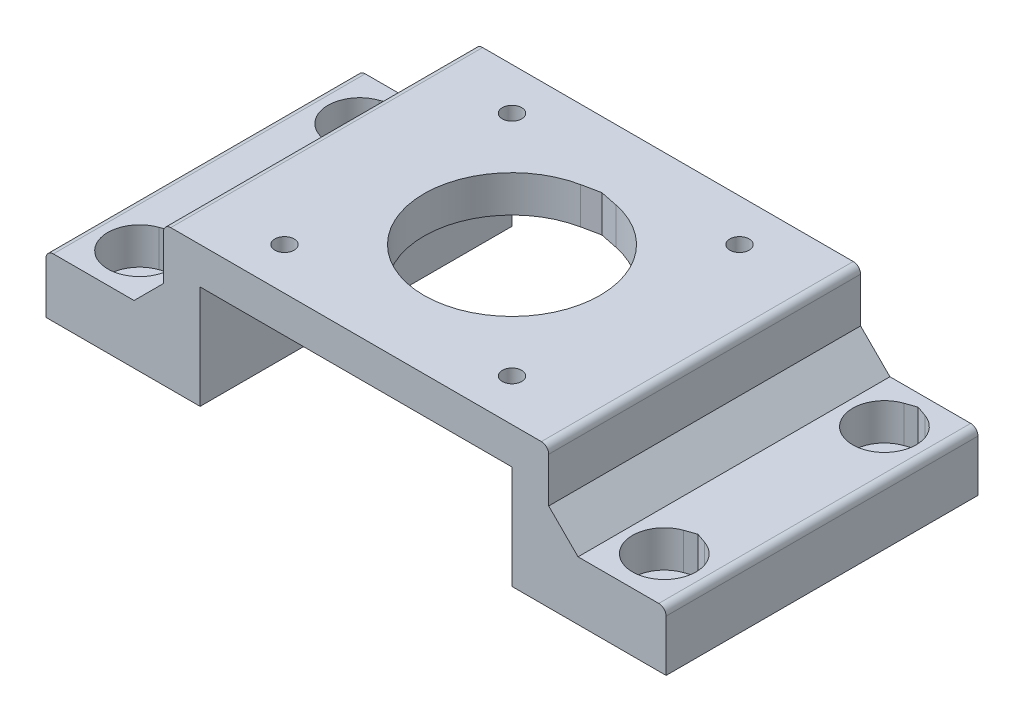
SolidWorks part; units mm, degrees
ref_plane "Plan de face" through (0, 0, 0) normal (0, 0, 1) x (1, 0, 0)
ref_plane "Plan de dessus" through (0, 0, 0) normal (0, 1, 0) x (1, 0, 0)
ref_plane "Plan de droite" through (0, 0, 0) normal (1, 0, 0) x (0, 0, -1)
sketch "Esquisse1" plane through (0, 0, 0) normal (0, 1, 0) x (1, 0, 0)
  line L1 (-21.25, -21.25) -> (21.25, -21.25)
  line L2 (-21.25, -21.25) -> (-21.25, 21.25)
  line L3 (-21.25, 21.25) -> (21.25, 21.25)
  line L4 (21.25, -21.25) -> (21.25, 21.25)
  line L5 (-21.25, -21.25) -> (21.25, 21.25) construction
  line L6 (-21.25, 21.25) -> (21.25, -21.25) construction
  point P0 (0, 0)
  dimension "D1" = 42.5
extrude "Boss.-Extru.1" add sketch "Esquisse1" along normal blind 5
sketch "Esquisse2" plane through (0, 5, 0) normal (0, 1, 0) x (1, 0, 0)
  line L0 (0, -19.1831) -> (0, 20.1838) construction
  line L1 (-17.0845, 0) -> (18.1385, 0) construction
  circle A1 centre (-15.5, 15.5) radius 1.325
  circle A2 centre (15.5, 15.5) radius 1.325
  dimension "D2" = 2.65
  dimension "D3" = 31
  dimension "D4" = 15.5
  dimension "D5" = 15.5
extrude "Enlèv. mat.-Extru.1" cut sketch "Esquisse2" against normal through all
mirror "Symétrie1" about plane through (0, 0, 0) normal (0, 0, 1) of "Enlèv. mat.-Extru.1"
sketch "Esquisse3" plane through (0, 5, 0) normal (0, 1, 0) x (1, 0, 0)
  line L1 (2.4241, 11.7526) -> (0, 12.2526)
  line L2 (0, 12.2526) -> (-2.4241, 11.7526)
  arc A0 (-2.4241, 11.7526) -> (2.4241, 11.7526) centre (0, 0) ccw
  dimension "D1" = 24
  dimension "D2" = 0.5
extrude "Enlèv. mat.-Extru.2" cut sketch "Esquisse3" against normal through all
sketch "Esquisse4" plane through (21.25, 0, 0) normal (1, 0, 0) x (0, 0, -1)
  line L0 (21.25, 5) -> (21.25, 0) construction
  line L1 (-21.25, 5) -> (21.25, 5)
  line L2 (-21.25, 5) -> (-21.25, -14.1)
  line L3 (-21.25, -14.1) -> (21.25, -14.1)
  line L4 (21.25, 5) -> (21.25, -14.1)
  dimension "D1" = 19.1
extrude "Boss.-Extru.2" add sketch "Esquisse4" along normal blind 5
sketch "Esquisse5" plane through (26.25, 0, 0) normal (1, 0, 0) x (0, 0, -1)
  line L0 (21.25, -14.1) -> (21.25, 5) construction
  line L1 (-21.25, -14.1) -> (21.25, -14.1)
  line L2 (-21.25, -14.1) -> (-21.25, -6.1)
  line L3 (-21.25, -6.1) -> (21.25, -6.1)
  line L4 (21.25, -14.1) -> (21.25, -6.1)
  dimension "D1" = 8
extrude "Boss.-Extru.3" add sketch "Esquisse5" along normal blind 16
sketch "Esquisse7" plane through (0, -6.1, 0) normal (0, 1, 0) x (1, 0, 0)
  line L0 (42.25, 21.25) -> (42.25, -21.25) construction
  circle A0 centre (35.75, 15) radius 2.6
  circle A1 centre (35.75, -15) radius 2.6
  dimension "D1" = 5.2
  dimension "D2" = 30
  dimension "D3" = 15
  dimension "D4" = 6.5
extrude "Enlèv. mat.-Extru.3" cut sketch "Esquisse7" against normal through all
fillet "Congé2" radius 1 2 edges at (42.25, -6.1, 0) (26.25, 5, 0)
chamfer "Chanfrein1" distance 4 angle 45 1 edges at (26.25, -6.1, 0)
mirror "Symétrie3" about plane through (0, 0, 0) normal (1, 0, 0) of "Chanfrein1", "Congé2", "Enlèv. mat.-Extru.3", "Boss.-Extru.3", "Boss.-Extru.2"
sketch "Esquisse11" plane through (0, -6.1, 0) normal (0, 1, 0) x (1, 0, 0)
  circle A0 centre (35.75, 15) radius 4.325
  dimension "D1" = 8.65
extrude "Enlèv. mat.-Extru.4" cut sketch "Esquisse11" against normal blind 5
mirror "Symétrie4" about plane through (0, 0, 0) normal (0, 0, 1) of "Enlèv. mat.-Extru.4"
sketch "Esquisse12" plane through (0, -6.1, 0) normal (0, 1, 0) x (1, 0, 0)
  line L0 (37.1787, 19.0822) -> (34.3213, 19.0822)
  line L1 (34.3213, 19.0822) -> (35.75, 19.5822)
  line L2 (35.75, 19.5822) -> (37.1787, 19.0822)
  line L3 (41.25, 21.25) -> (30.25, 21.25) construction
  circle A0 centre (35.75, 15) radius 4.325 construction
  dimension "D1" = 0.5
extrude "Enlèv. mat.-Extru.5" cut sketch "Esquisse12" against normal up to surface (5 mm away) up to face at (35.75, -11.1, -10.675)
sketch "Esquisse13" plane through (0, -11.1, 0) normal (0, 1, 0) x (1, 0, 0)
  line L0 (34.6633, 17.362) -> (36.8367, 17.362)
  line L1 (36.8367, 17.362) -> (35.75, 17.862)
  line L2 (35.75, 17.862) -> (34.6633, 17.362)
  line L3 (41.25, 21.25) -> (30.25, 21.25) construction
  circle A0 centre (35.75, 15) radius 2.6 construction
  dimension "D1" = 0.5
extrude "Enlèv. mat.-Extru.6" cut sketch "Esquisse13" against normal through all
sketch "Esquisse14" plane through (0, -11.1, 0) normal (0, 1, 0) x (1, 0, 0)
  line L0 (36.8367, -12.638) -> (35.75, -12.138)
  line L1 (35.75, -12.138) -> (34.6633, -12.638)
  line L2 (34.6633, -12.638) -> (36.8367, -12.638)
  line L3 (41.25, -21.25) -> (30.25, -21.25) construction
  circle A0 centre (35.75, -15) radius 2.6 construction
  dimension "D1" = 0.5
extrude "Enlèv. mat.-Extru.7" cut sketch "Esquisse14" against normal through all
sketch "Esquisse15" plane through (0, -6.1, 0) normal (0, 1, 0) x (1, 0, 0)
  line L0 (34.3213, -10.9178) -> (37.1787, -10.9178)
  line L1 (37.1787, -10.9178) -> (35.75, -10.4178)
  line L2 (35.75, -10.4178) -> (34.3213, -10.9178)
  line L3 (41.25, -21.25) -> (30.25, -21.25) construction
  circle A0 centre (35.75, -15) radius 4.325 construction
  circle A1 centre (35.75, -15) radius 4.325 construction
  dimension "D1" = 0.5
extrude "Enlèv. mat.-Extru.8" cut sketch "Esquisse15" against normal up to surface (5 mm away) up to face at (35.75, -11.1, 14.1253)
mirror "Symétrie5" about plane through (0, 0, 0) normal (1, 0, 0) of "Symétrie4", "Enlèv. mat.-Extru.4", "Enlèv. mat.-Extru.7", "Enlèv. mat.-Extru.5", "Enlèv. mat.-Extru.6", "Enlèv. mat.-Extru.8"
